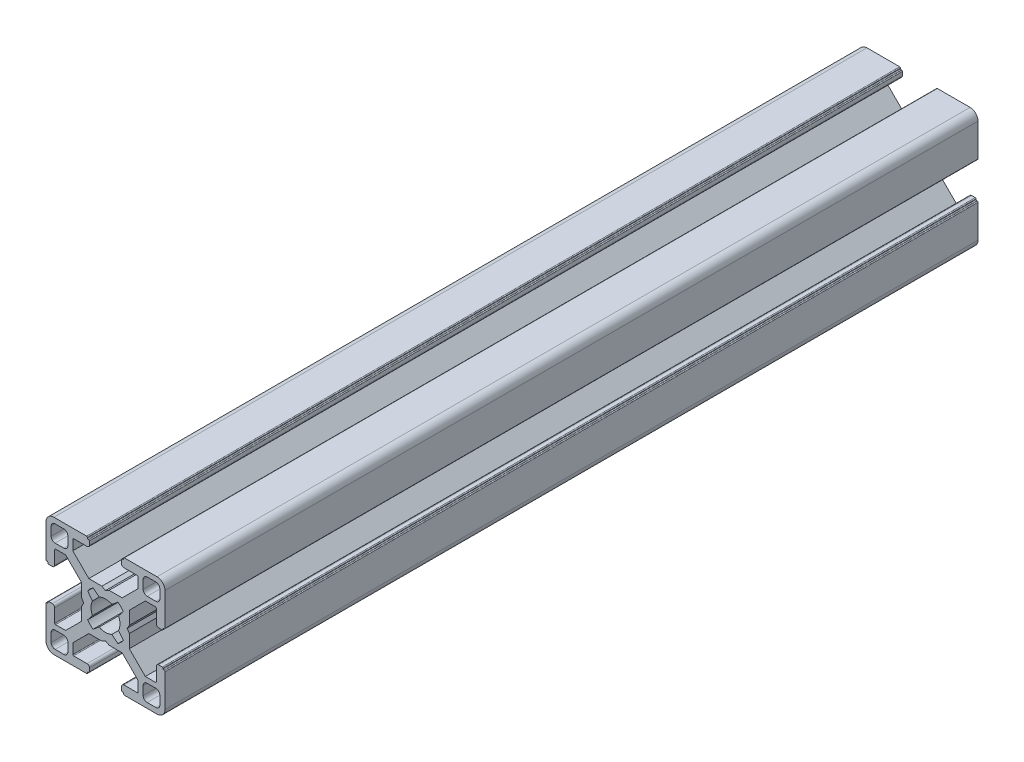
SolidWorks part; units mm, degrees
material "6061 Alloy"
ref_plane "Front" through (0, 0, 0) normal (0, 0, 1) x (1, 0, 0)
ref_plane "Top" through (0, 0, 0) normal (0, 1, 0) x (1, 0, 0)
ref_plane "Right" through (0, 0, 0) normal (1, 0, 0) x (0, 0, -1)
sketch "Sketch1" plane through (0, 0, 0) normal (0, 0, 1) x (1, 0, 0)
  line L0 (13.7, 12.7) -> (13.7, 10.5)
  line L1 (10.5, 9.5) -> (12.7, 9.5)
  line L2 (9.5, 12.7) -> (9.5, 10.5)
  line L3 (10.5, 13.7) -> (12.7, 13.7)
  line L4 (3.1359, 4.5184) -> (1.6001, 3.2806)
  line L5 (3.2806, 1.6001) -> (4.5053, 3.1547)
  line L6 (6.0045, 0.9) -> (5.4849, 0)
  line L7 (6.0045, 4.2045) -> (6.0045, 0.9)
  line L8 (0, -5.4849) -> (0.9, -6)
  line L9 (0.9, -6) -> (4.2045, -6)
  line L10 (4.2045, -6) -> (8.25, -10.05)
  line L11 (8.25, -10.05) -> (8.25, -12.6)
  line L12 (4.65, -12.8) -> (8.05, -12.8)
  line L13 (4.05, -14.3) -> (4.05, -13.4)
  line L14 (4.25, -14.5) -> (4.35, -14.5)
  line L15 (4.55, -14.8) -> (4.55, -14.7)
  line L16 (4.75, -15) -> (13, -15)
  line L17 (15, -13) -> (15, -4.75)
  line L18 (14.7, -4.55) -> (14.8, -4.55)
  line L19 (14.5, -4.35) -> (14.5, -4.25)
  line L20 (13.4, -4.05) -> (14.3, -4.05)
  line L21 (12.8, -8.05) -> (12.8, -4.65)
  line L22 (12.6, -8.25) -> (10.05, -8.25)
  line L23 (10.05, -8.25) -> (6.0045, -4.2045)
  line L24 (6.0045, -4.2045) -> (6.0045, -0.9)
  line L25 (6.0045, -0.9) -> (5.4849, 0)
  line L26 (10.05, 8.25) -> (6.0045, 4.2045)
  line L27 (12.6, 8.25) -> (10.05, 8.25)
  line L28 (12.8, 8.05) -> (12.8, 4.65)
  line L29 (13.4, 4.05) -> (14.3, 4.05)
  line L30 (14.5, 4.35) -> (14.5, 4.25)
  line L31 (14.7, 4.55) -> (14.8, 4.55)
  line L32 (15, 13) -> (15, 4.75)
  line L33 (4.75, 15) -> (13, 15)
  line L34 (4.55, 14.8) -> (4.55, 14.7)
  line L35 (4.25, 14.5) -> (4.35, 14.5)
  line L36 (4.05, 14.3) -> (4.05, 13.4)
  line L37 (4.65, 12.8) -> (8.05, 12.8)
  line L38 (8.25, 10.05) -> (8.25, 12.6)
  line L39 (4.2045, 6) -> (8.25, 10.05)
  line L40 (0.9, 6) -> (4.2045, 6)
  line L41 (0, 5.4849) -> (0.9, 6)
  line L42 (-13.7, -12.7) -> (-13.7, -10.5)
  line L43 (-10.5, -9.5) -> (-12.7, -9.5)
  line L44 (-9.5, -12.7) -> (-9.5, -10.5)
  line L45 (-10.5, -13.7) -> (-12.7, -13.7)
  line L46 (-3.1359, -4.5184) -> (-1.6001, -3.2806)
  line L47 (-3.2806, -1.6001) -> (-4.5053, -3.1547)
  line L48 (0, 5.4849) -> (-0.9, 6)
  line L49 (-0.9, 6) -> (-4.2045, 6)
  line L50 (-4.2045, 6) -> (-8.25, 10.05)
  line L51 (-8.25, 10.05) -> (-8.25, 12.6)
  line L52 (-4.65, 12.8) -> (-8.05, 12.8)
  line L53 (-4.05, 14.3) -> (-4.05, 13.4)
  line L54 (-4.25, 14.5) -> (-4.35, 14.5)
  line L55 (-4.55, 14.8) -> (-4.55, 14.7)
  line L56 (-4.75, 15) -> (-13, 15)
  line L57 (-15, 13) -> (-15, 4.75)
  line L58 (-14.7, 4.55) -> (-14.8, 4.55)
  line L59 (-14.5, 4.35) -> (-14.5, 4.25)
  line L60 (-13.4, 4.05) -> (-14.3, 4.05)
  line L61 (-12.8, 8.05) -> (-12.8, 4.65)
  line L62 (-12.6, 8.25) -> (-10.05, 8.25)
  line L63 (-10.05, 8.25) -> (-6.0045, 4.2045)
  line L64 (-6.0045, -0.9) -> (-5.4849, 0)
  line L65 (-6.0045, -4.2045) -> (-6.0045, -0.9)
  line L66 (-10.05, -8.25) -> (-6.0045, -4.2045)
  line L67 (-12.6, -8.25) -> (-10.05, -8.25)
  line L68 (-12.8, -8.05) -> (-12.8, -4.65)
  line L69 (-13.4, -4.05) -> (-14.3, -4.05)
  line L70 (-14.5, -4.35) -> (-14.5, -4.25)
  line L71 (-14.7, -4.55) -> (-14.8, -4.55)
  line L72 (-15, -13) -> (-15, -4.75)
  line L73 (-4.75, -15) -> (-13, -15)
  line L74 (-4.55, -14.8) -> (-4.55, -14.7)
  line L75 (-4.25, -14.5) -> (-4.35, -14.5)
  line L76 (-4.05, -14.3) -> (-4.05, -13.4)
  line L77 (3.2806, -1.6001) -> (4.5053, -3.1547)
  line L78 (3.1359, -4.5184) -> (1.6001, -3.2806)
  line L79 (-4.65, -12.8) -> (-8.05, -12.8)
  line L80 (-8.25, -10.05) -> (-8.25, -12.6)
  line L81 (-4.2045, -6) -> (-8.25, -10.05)
  line L82 (-0.9, -6) -> (-4.2045, -6)
  line L83 (0, -5.4849) -> (-0.9, -6)
  line L84 (10.5, -13.7) -> (12.7, -13.7)
  line L85 (9.5, -12.7) -> (9.5, -10.5)
  line L86 (10.5, -9.5) -> (12.7, -9.5)
  line L87 (13.7, -12.7) -> (13.7, -10.5)
  line L88 (-6.0045, 4.2045) -> (-6.0045, 0.9)
  line L89 (-6.0045, 0.9) -> (-5.4849, 0)
  line L90 (-3.2806, 1.6001) -> (-4.5053, 3.1547)
  line L91 (-3.1359, 4.5184) -> (-1.6001, 3.2806)
  line L92 (-10.5, 13.7) -> (-12.7, 13.7)
  line L93 (-9.5, 12.7) -> (-9.5, 10.5)
  line L94 (-10.5, 9.5) -> (-12.7, 9.5)
  line L95 (-13.7, 12.7) -> (-13.7, 10.5)
  line L96 (-23.4857, 0) -> (20.9308, 0) construction
  line L97 (0, 17.9563) -> (0, -17.361) construction
  arc A0 (13.7, 12.7) -> (12.7, 13.7) centre (12.7, 12.7) ccw
  arc A1 (12.7, 9.5) -> (13.7, 10.5) centre (12.7, 10.5) ccw
  arc A2 (9.5, 10.5) -> (10.5, 9.5) centre (10.5, 10.5) ccw
  arc A3 (10.5, 13.7) -> (9.5, 12.7) centre (10.5, 12.7) ccw
  arc A4 (1.6001, 3.2806) -> (-1.6001, 3.2806) centre (0, 0) ccw
  arc A5 (8.25, -12.6) -> (8.05, -12.8) centre (8.05, -12.6) cw
  arc A6 (4.65, -12.8) -> (4.05, -13.4) centre (4.65, -13.4) ccw
  arc A7 (4.05, -14.3) -> (4.25, -14.5) centre (4.25, -14.3) ccw
  arc A8 (4.35, -14.5) -> (4.55, -14.7) centre (4.35, -14.7) cw
  arc A9 (4.55, -14.8) -> (4.75, -15) centre (4.75, -14.8) ccw
  arc A10 (13, -15) -> (15, -13) centre (13, -13) ccw
  arc A11 (15, -4.75) -> (14.8, -4.55) centre (14.8, -4.75) ccw
  arc A12 (14.7, -4.55) -> (14.5, -4.35) centre (14.7, -4.35) cw
  arc A13 (14.5, -4.25) -> (14.3, -4.05) centre (14.3, -4.25) ccw
  arc A14 (13.4, -4.05) -> (12.8, -4.65) centre (13.4, -4.65) ccw
  arc A15 (12.8, -8.05) -> (12.6, -8.25) centre (12.6, -8.05) cw
  arc A16 (4.5053, 3.1547) -> (3.1359, 4.5184) centre (0, 0) ccw
  arc A17 (12.8, 8.05) -> (12.6, 8.25) centre (12.6, 8.05) ccw
  arc A18 (13.4, 4.05) -> (12.8, 4.65) centre (13.4, 4.65) cw
  arc A19 (14.5, 4.25) -> (14.3, 4.05) centre (14.3, 4.25) cw
  arc A20 (14.7, 4.55) -> (14.5, 4.35) centre (14.7, 4.35) ccw
  arc A21 (15, 4.75) -> (14.8, 4.55) centre (14.8, 4.75) cw
  arc A22 (13, 15) -> (15, 13) centre (13, 13) cw
  arc A23 (4.55, 14.8) -> (4.75, 15) centre (4.75, 14.8) cw
  arc A24 (4.35, 14.5) -> (4.55, 14.7) centre (4.35, 14.7) ccw
  arc A25 (4.05, 14.3) -> (4.25, 14.5) centre (4.25, 14.3) cw
  arc A26 (4.65, 12.8) -> (4.05, 13.4) centre (4.65, 13.4) cw
  arc A27 (8.25, 12.6) -> (8.05, 12.8) centre (8.05, 12.6) ccw
  arc A28 (-13.7, -12.7) -> (-12.7, -13.7) centre (-12.7, -12.7) ccw
  arc A29 (-12.7, -9.5) -> (-13.7, -10.5) centre (-12.7, -10.5) ccw
  arc A30 (-9.5, -10.5) -> (-10.5, -9.5) centre (-10.5, -10.5) ccw
  arc A31 (-10.5, -13.7) -> (-9.5, -12.7) centre (-10.5, -12.7) ccw
  arc A32 (-4.5053, -3.1547) -> (-3.1359, -4.5184) centre (0, 0) ccw
  arc A33 (-3.2806, 1.6001) -> (-3.2806, -1.6001) centre (0, 0) ccw
  arc A34 (-8.25, 12.6) -> (-8.05, 12.8) centre (-8.05, 12.6) cw
  arc A35 (-4.65, 12.8) -> (-4.05, 13.4) centre (-4.65, 13.4) ccw
  arc A36 (-4.05, 14.3) -> (-4.25, 14.5) centre (-4.25, 14.3) ccw
  arc A37 (-4.35, 14.5) -> (-4.55, 14.7) centre (-4.35, 14.7) cw
  arc A38 (-4.55, 14.8) -> (-4.75, 15) centre (-4.75, 14.8) ccw
  arc A39 (-13, 15) -> (-15, 13) centre (-13, 13) ccw
  arc A40 (-15, 4.75) -> (-14.8, 4.55) centre (-14.8, 4.75) ccw
  arc A41 (-14.7, 4.55) -> (-14.5, 4.35) centre (-14.7, 4.35) cw
  arc A42 (-14.5, 4.25) -> (-14.3, 4.05) centre (-14.3, 4.25) ccw
  arc A43 (-13.4, 4.05) -> (-12.8, 4.65) centre (-13.4, 4.65) ccw
  arc A44 (-12.8, 8.05) -> (-12.6, 8.25) centre (-12.6, 8.05) cw
  arc A45 (-4.5053, 3.1547) -> (-3.1359, 4.5184) centre (0, 0) cw
  arc A46 (-12.8, -8.05) -> (-12.6, -8.25) centre (-12.6, -8.05) ccw
  arc A47 (-13.4, -4.05) -> (-12.8, -4.65) centre (-13.4, -4.65) cw
  arc A48 (-14.5, -4.25) -> (-14.3, -4.05) centre (-14.3, -4.25) cw
  arc A49 (3.2806, 1.6001) -> (3.2806, -1.6001) centre (0, 0) cw
  arc A50 (4.5053, -3.1547) -> (3.1359, -4.5184) centre (0, 0) cw
  arc A51 (1.6001, -3.2806) -> (-1.6001, -3.2806) centre (0, 0) cw
  arc A52 (-14.7, -4.55) -> (-14.5, -4.35) centre (-14.7, -4.35) ccw
  arc A53 (-15, -4.75) -> (-14.8, -4.55) centre (-14.8, -4.75) cw
  arc A54 (-13, -15) -> (-15, -13) centre (-13, -13) cw
  arc A55 (-4.55, -14.8) -> (-4.75, -15) centre (-4.75, -14.8) cw
  arc A56 (10.5, -13.7) -> (9.5, -12.7) centre (10.5, -12.7) cw
  arc A57 (9.5, -10.5) -> (10.5, -9.5) centre (10.5, -10.5) cw
  arc A58 (12.7, -9.5) -> (13.7, -10.5) centre (12.7, -10.5) cw
  arc A59 (13.7, -12.7) -> (12.7, -13.7) centre (12.7, -12.7) cw
  arc A60 (-4.35, -14.5) -> (-4.55, -14.7) centre (-4.35, -14.7) ccw
  arc A61 (-4.05, -14.3) -> (-4.25, -14.5) centre (-4.25, -14.3) cw
  arc A62 (-4.65, -12.8) -> (-4.05, -13.4) centre (-4.65, -13.4) cw
  arc A63 (-8.25, -12.6) -> (-8.05, -12.8) centre (-8.05, -12.6) ccw
  arc A64 (-10.5, 13.7) -> (-9.5, 12.7) centre (-10.5, 12.7) cw
  arc A65 (-9.5, 10.5) -> (-10.5, 9.5) centre (-10.5, 10.5) cw
  arc A66 (-12.7, 9.5) -> (-13.7, 10.5) centre (-12.7, 10.5) cw
  arc A67 (-13.7, 12.7) -> (-12.7, 13.7) centre (-12.7, 12.7) cw
  point P81 (15, 15)
  point P82 (0, 15)
  point P203 (0, -15)
  point P204 (15, -15)
  point P206 (0, 0)
  point P207 (15, 0)
  point P219 (-15, 0)
  point P220 (-15, -15)
  point P221 (-15, 15)
extrude "Base-Extrude" add sketch "Sketch1" against normal blind 205
sketch "草图2" plane through (15, 0, 0) normal (1, 0, 0) x (0, 0, -1)
  line L0 (0, 15) -> (30, -15)
  line L1 (205, -15) -> (0, -15) construction
  line L2 (0, 4.75) -> (0, 13) construction
  line L3 (0, 15) -> (0, -15)
  line L4 (0, -15) -> (30, -15)
  line L5 (-13.0087, 11.9543) -> (-11.263, 12.8943)
  dimension "D1" = 45
